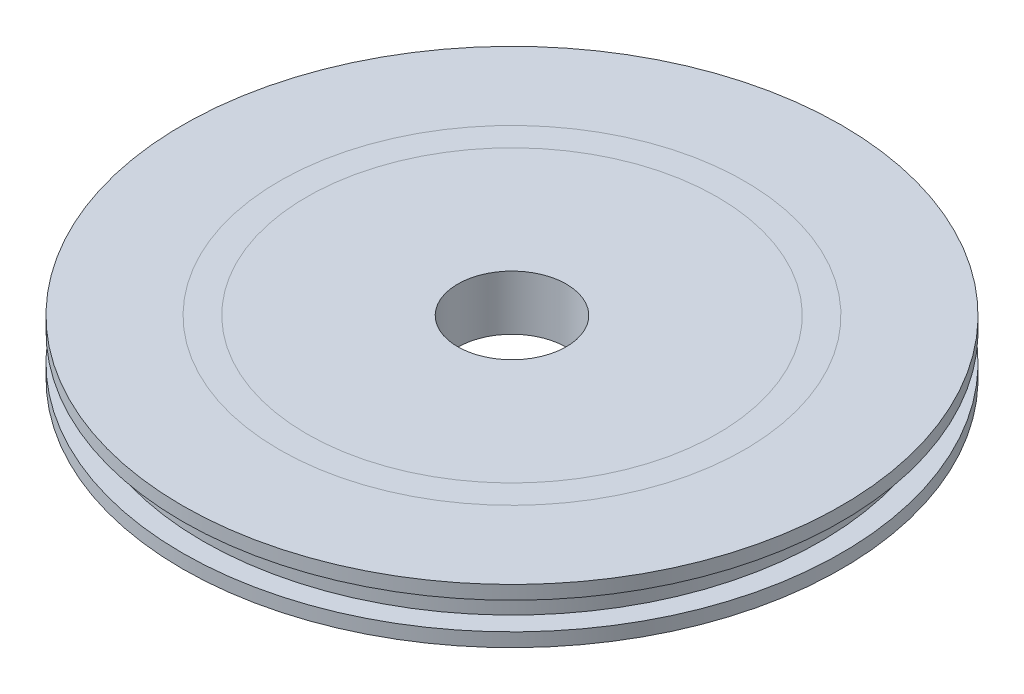
SolidWorks part; units mm, degrees
material "6061-T6 (SS)"
ref_plane "X-Y Datum" through (0, 0, 0) normal (0, 0, 1) x (1, 0, 0)
ref_plane "X-Z Datum" through (0, 0, 0) normal (0, 1, 0) x (1, 0, 0)
ref_plane "Y-Z Datum" through (0, 0, 0) normal (1, 0, 0) x (0, 0, -1)
sketch "Sketch1" plane through (0, 0, 0) normal (1, 0, 0) x (0, 0, -1)
  line L0 (0, 0) -> (0, -32027.2037) construction
  line L1 (0, 0) -> (0, -5.08)
  line L2 (0, -5.08) -> (-30.5867, -5.08)
  line L3 (-30.5867, -5.08) -> (-30.5867, -3.81)
  line L4 (-30.5867, -3.81) -> (-28.6817, -3.81)
  line L5 (-28.6817, -3.81) -> (-28.6817, -1.27)
  line L6 (-28.6817, -1.27) -> (-30.5867, -1.27)
  line L7 (-30.5867, -1.27) -> (-30.5867, 0)
  line L8 (-30.5867, 0) -> (0, 0)
  dimension "D1" = 61.1734
  dimension "D2" = 5.08
  dimension "D3" = 2.54
  dimension "D5" = 57.3634
revolve "Revolve1" add sketch "Sketch1" angle 360 about L0
sketch "Sketch2" plane through (0, 0, 0) normal (0, 1, 0) x (1, 0, 0)
  circle A0 centre (0, 0) radius 19.05
  dimension "D1" = 38.1
split line "Split Line1"
sketch "Sketch3" plane through (0, 0, 0) normal (0, 1, 0) x (1, 0, 0)
  circle A0 centre (0, 0) radius 21.59
  dimension "D1" = 43.18
split line "Split Line2"
hole_wizard "Ø10.0mm Dowel Hole1" positions "Sketch4" profile "Sketch5" hole size "Ø10.0" standard "ANSI Metric"
sketch "Sketch4" plane through (0, 0, 0) normal (0, 1, 0) x (1, 0, 0)
  point P0 (0, 0)
sketch "Sketch5" plane through (0, 0, 0) normal (1, 0, 0) x (0, 0, 1)
  line L0 (0, 0) -> (0, 5.08)
  line L1 (0, 5.08) -> (5, 5.08)
  line L2 (5, 5.08) -> (5, 0)
  line L5 (5, 0) -> (0, 0)
  line L11 (0, -6.35) -> (0, 107.95) construction
  dimension "Thru Hole Dia." = 10
  dimension "Thru Hole Depth" = 5.08
sketch "Sketch6" plane through (0, -5.08, 0) normal (0, -1, 0) x (1, 0, 0)
  circle A0 centre (0, 0) radius 5.0419
  dimension "D1" = 10.0838
extrude "Cut-Extrude1" cut sketch "Sketch6" against normal through all
